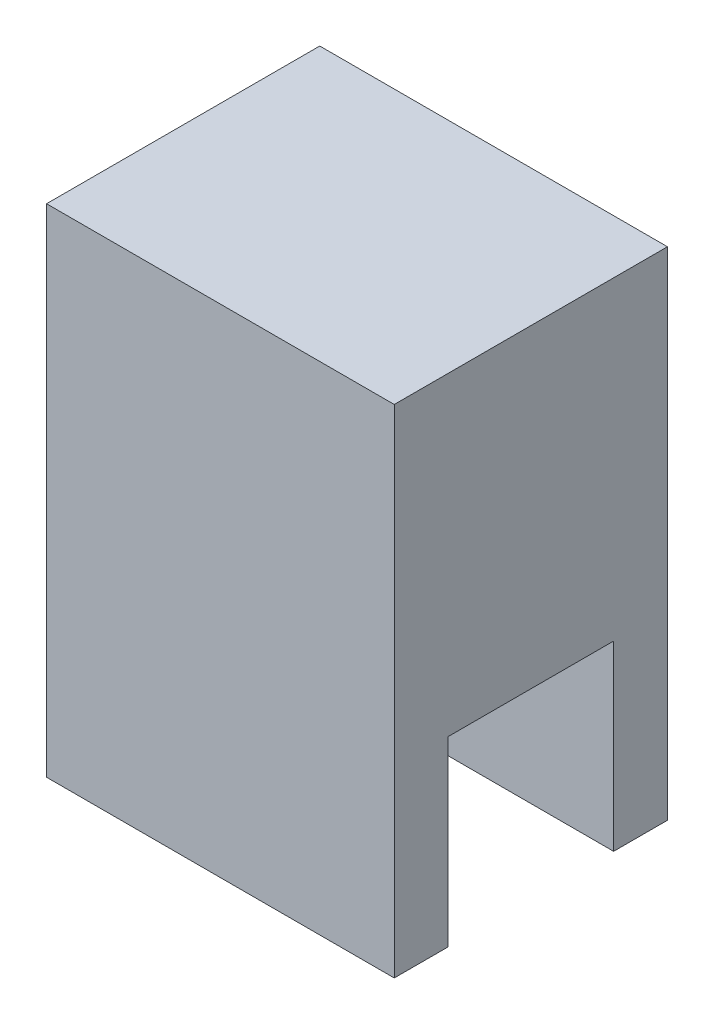
SolidWorks part; units mm, degrees
ref_plane "Front Plane" through (0, 0, 0) normal (0, 0, 1) x (1, 0, 0)
ref_plane "Top Plane" through (0, 0, 0) normal (0, 1, 0) x (1, 0, 0)
ref_plane "Right Plane" through (0, 0, 0) normal (1, 0, 0) x (0, 0, -1)
sketch "Sketch1" plane through (0, 0, 0) normal (0, 1, 0) x (1, 0, 0)
  line L1 (-21, 16.5) -> (21, 16.5)
  line L2 (-21, 16.5) -> (-21, -16.5)
  line L3 (-21, -16.5) -> (21, -16.5)
  line L4 (21, 16.5) -> (21, -16.5)
  line L5 (-21, 16.5) -> (21, -16.5) construction
  line L6 (-21, -16.5) -> (21, 16.5) construction
  point P0 (0, 0)
  dimension "D1" = 42
  dimension "D2" = 33
extrude "Boss-Extrude1" add sketch "Sketch1" along normal mid plane 60
sketch "Sketch2" plane through (0, 0, 0) normal (1, 0, 0) x (0, 0, -1)
  line L0 (-16.5, -30) -> (16.5, -30) construction
  line L1 (-10, -30) -> (10, -30)
  line L2 (-10, -30) -> (-10, -8)
  line L3 (-10, -8) -> (10, -8)
  line L4 (10, -30) -> (10, -8)
  point P6 (0, -8)
  dimension "D1" = 22
  dimension "D2" = 20
extrude "Cut-Extrude1" cut sketch "Sketch2" against normal through all both and the other way through all
